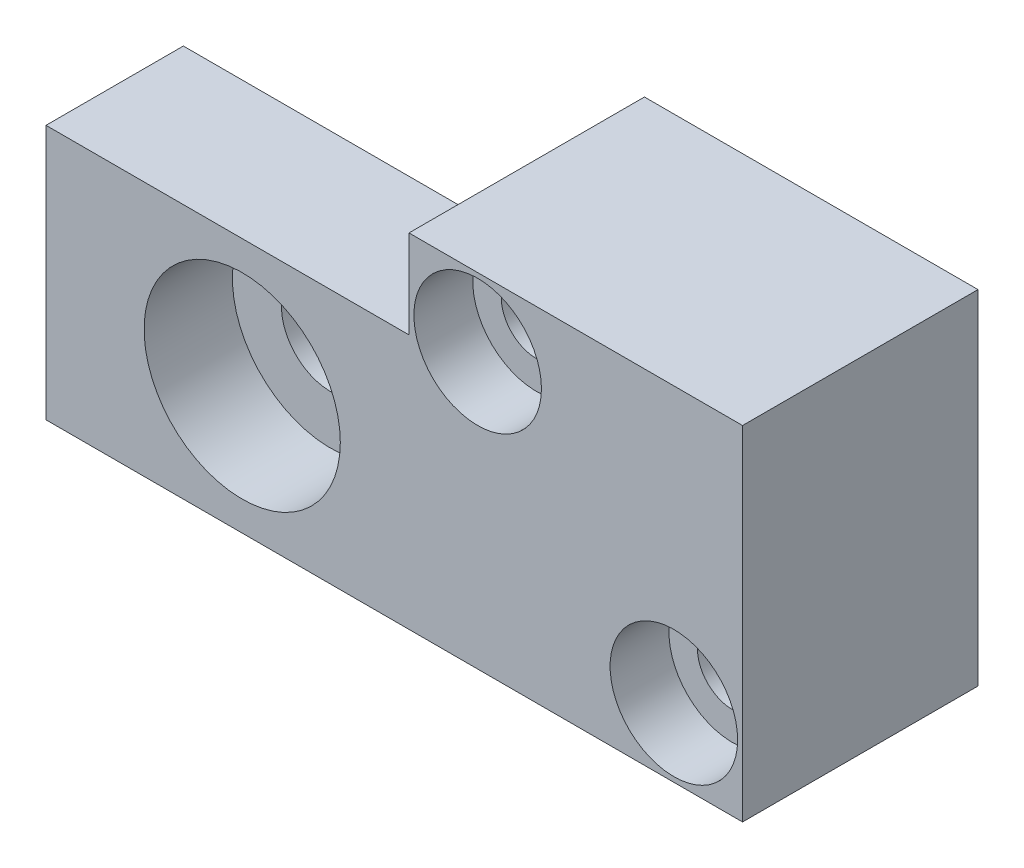
SolidWorks part; units mm, degrees
material "SKD11淬火HRC56-60"
ref_plane "前基準面" through (0, 0, 0) normal (0, 0, 1) x (1, 0, 0)
ref_plane "上基準面" through (0, 0, 0) normal (0, 1, 0) x (1, 0, 0)
ref_plane "右基準面" through (0, 0, 0) normal (1, 0, 0) x (0, 0, -1)
sketch "草图1" plane through (0, 0, 0) normal (0, 0, 1) x (1, 0, 0)
  line L1 (0, 0) -> (35.5, 0)
  line L2 (0, 0) -> (0, 17.5)
  line L3 (0, 17.5) -> (35.5, 17.5)
  line L4 (35.5, 0) -> (35.5, 17.5)
  dimension "D1" = 35.5
  dimension "D2" = 17.5
extrude "凸台-拉伸1" add sketch "草图1" along normal blind 12
sketch "草图2" plane through (0, 0, 12) normal (0, 0, 1) x (1, 0, 0)
  line L1 (0, 17.5) -> (18.5, 17.5)
  line L2 (0, 17.5) -> (0, 13)
  line L3 (0, 13) -> (18.5, 13)
  line L4 (18.5, 17.5) -> (18.5, 13)
  dimension "D1" = 18.5
  dimension "D2" = 4.5
extrude "切除-拉伸1" cut sketch "草图2" against normal through all
sketch "草图3" plane through (0, 0, 12) normal (0, 0, 1) x (1, 0, 0)
  line L0 (0, 13) -> (0, 0) construction
  line L1 (0, 0) -> (35.5, 0) construction
  circle A0 centre (10, 6.5) radius 5
  dimension "D1" = 10
  dimension "D2" = 10
  dimension "D3" = 6.5
extrude "切除-拉伸2" cut sketch "草图3" against normal blind 4.5
hole_wizard "M3 六角凹头螺钉的柱形沉头孔1" positions "草图7" profile "草图6" counterbore size "M3" standard "ISO" end condition through all
sketch "草图7" plane through (0, 0, 12) normal (0, 0, 1) x (1, 0, 0)
  point P0 (22, 14)
  point P1 (32, 3.5)
sketch "草图6" plane through (22, 14, 12) normal (1, 0, 0) x (0, -1, 0)
  line L0 (0, 0) -> (0, 12)
  line L1 (0, 12) -> (1.8, 12)
  line L3 (1.8, 12) -> (1.8, 3)
  line L4 (1.8, 3) -> (3.25, 3)
  line L5 (3.25, 3) -> (3.25, 0)
  line L7 (3.25, 0) -> (0, 0)
  line L11 (0, -6.35) -> (0, 107.95) construction
  dimension "通孔孔直径" = 3.6
  dimension "通孔孔深度" = 12
  dimension "柱形沉头孔直径" = 6.5
  dimension "柱形沉头孔深度" = 3
sketch "草图8" plane through (0, 0, 7.5) normal (0, 0, 1) x (1, 0, 0)
  circle A0 centre (10, 6.5) radius 2.5
  dimension "D1" = 5
extrude "切除-拉伸3" cut sketch "草图8" against normal through all
sketch "草图10" plane through (0, 0, 0) normal (0, 0, -1) x (-1, 0, 0)
  line L1 (0, 0) -> (-17, 0)
  line L2 (0, 0) -> (0, 13)
  line L3 (0, 13) -> (-17, 13)
  line L4 (-17, 0) -> (-17, 13)
  line L5 (0, 13) -> (-18.5, 13) construction
  dimension "D1" = 17
extrude "切除-拉伸4" cut sketch "草图10" against normal blind 5
